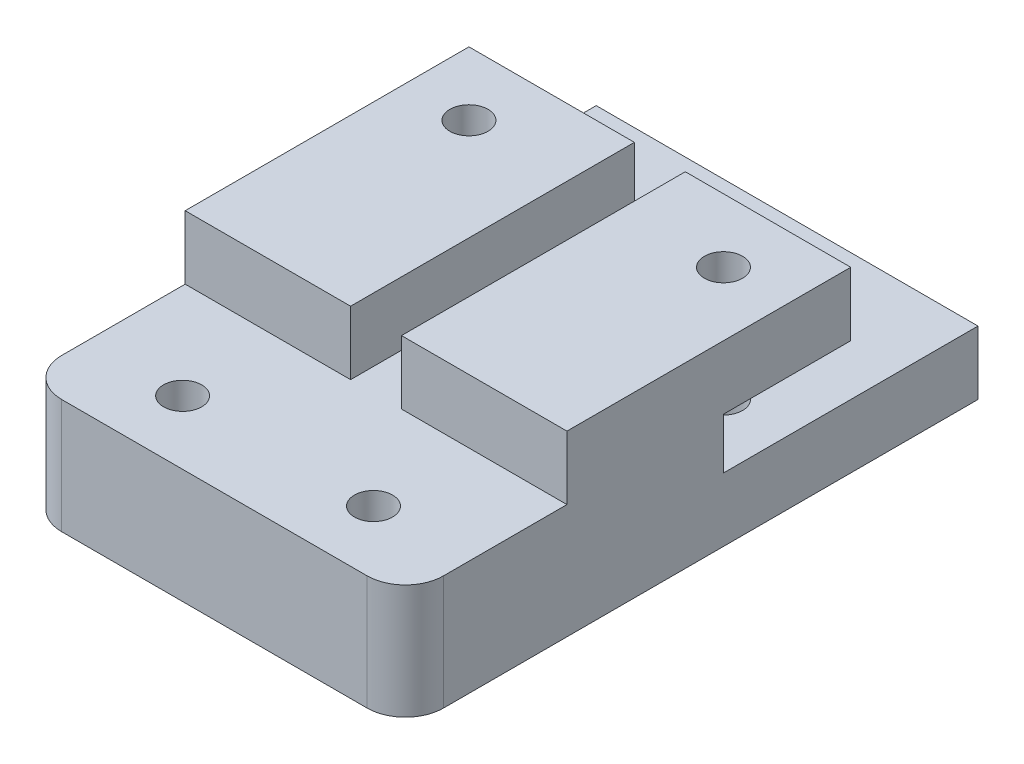
SolidWorks part; units mm, degrees
ref_plane "Alzado" through (0, 0, 0) normal (0, 0, 1) x (1, 0, 0)
ref_plane "Planta" through (0, 0, 0) normal (0, 1, 0) x (1, 0, 0)
ref_plane "Vista lateral" through (0, 0, 0) normal (1, 0, 0) x (0, 0, -1)
sketch "Croquis1" plane through (0, 0, 0) normal (0, 1, 0) x (1, 0, 0)
  line L0 (0, 30) -> (5, 30) construction
  line L1 (0, 0) -> (30, 0)
  line L2 (0, 0) -> (0, 35)
  line L3 (0, 35) -> (30, 35)
  line L4 (30, 0) -> (30, 35)
  line L5 (5, 30) -> (25, 30) construction
  line L6 (25, 30) -> (30, 30) construction
  line L7 (15, 30) -> (15, 35) construction
  line L8 (0, 5) -> (7.5, 5) construction
  line L9 (7.5, 5) -> (22.5, 5) construction
  line L10 (22.5, 5) -> (30, 5) construction
  line L11 (15, 30) -> (15, 5) construction
  circle A0 centre (25, 30) radius 1.5
  circle A1 centre (5, 30) radius 1.5
  circle A2 centre (7.5, 5) radius 1.5
  circle A3 centre (22.5, 5) radius 1.5
  dimension "D3" = 3
  dimension "D6" = 3
  dimension "D1" = 30
  dimension "D2" = 35
  dimension "D4" = 20
  dimension "D5" = 5
  dimension "D7" = 15
  dimension "D8" = 5
extrude "Saliente-Extruir1" add sketch "Croquis1" along normal blind 20
sketch "Croquis2" plane through (30, 0, 0) normal (1, 0, 0) x (0, 0, -1)
  line L0 (35, 20) -> (35, 0) construction
  line L1 (35, 11) -> (25, 11)
  line L2 (35, 11) -> (35, 15)
  line L3 (35, 15) -> (25, 15)
  line L4 (25, 11) -> (25, 15)
  line L5 (0, 20) -> (35, 20) construction
  dimension "D1" = 10
  dimension "D2" = 4
  dimension "D3" = 5
extrude "Cortar-Extruir1" cut sketch "Croquis2" against normal blind 41
sketch "Croquis3" plane through (0, 0, 0) normal (0, -1, 0) x (1, 0, 0)
  line L1 (5, -33.1177) -> (7.7, -31.5588)
  line L2 (7.7, -31.5588) -> (7.7, -28.4412)
  line L3 (7.7, -28.4412) -> (5, -26.8823)
  line L4 (5, -26.8823) -> (2.3, -28.4412)
  line L5 (2.3, -28.4412) -> (2.3, -31.5588)
  line L6 (2.3, -31.5588) -> (5, -33.1177)
  line L7 (25, -33.1177) -> (27.7, -31.5588)
  line L8 (27.7, -31.5588) -> (27.7, -28.4412)
  line L9 (27.7, -28.4412) -> (25, -26.8823)
  line L10 (25, -26.8823) -> (22.3, -28.4412)
  line L11 (22.3, -28.4412) -> (22.3, -31.5588)
  line L12 (22.3, -31.5588) -> (25, -33.1177)
  circle A0 centre (5, -30) radius 2.7 construction
  circle A1 centre (25, -30) radius 2.7 construction
  dimension "D1" = 5.4
extrude "Cortar-Extruir2" cut sketch "Croquis3" against normal blind 8
sketch "Croquis4" plane through (0, 0, 0) normal (0, -1, 0) x (1, 0, 0)
  line L1 (7.5, -8.1177) -> (10.2, -6.5588)
  line L2 (10.2, -6.5588) -> (10.2, -3.4412)
  line L3 (10.2, -3.4412) -> (7.5, -1.8823)
  line L4 (7.5, -1.8823) -> (4.8, -3.4412)
  line L5 (4.8, -3.4412) -> (4.8, -6.5588)
  line L6 (4.8, -6.5588) -> (7.5, -8.1177)
  line L7 (22.5, -8.1177) -> (25.2, -6.5588)
  line L8 (25.2, -6.5588) -> (25.2, -3.4412)
  line L9 (25.2, -3.4412) -> (22.5, -1.8823)
  line L10 (22.5, -1.8823) -> (19.8, -3.4412)
  line L11 (19.8, -3.4412) -> (19.8, -6.5588)
  line L12 (19.8, -6.5588) -> (22.5, -8.1177)
  circle A0 centre (7.5, -5) radius 2.7 construction
  circle A1 centre (22.5, -5) radius 2.7 construction
  dimension "D1" = 5.4
extrude "Cortar-Extruir3" cut sketch "Croquis4" against normal blind 8
sketch "Croquis6" plane through (0, 0, -35) normal (0, 0, -1) x (-1, 0, 0)
  line L4 (0, 0) -> (0, 11)
  line L5 (0, 11) -> (-30, 11)
  line L6 (-30, 11) -> (-30, 0)
  line L7 (-30, 0) -> (0, 0)
  line L8 (0, 0) -> (0, 11)
  line L9 (0, 11) -> (-30, 11)
  line L10 (-30, 11) -> (-30, 0)
  line L11 (-30, 0) -> (0, 0)
  dimension "D1" = 0
extrude "Saliente-Extruir2" add sketch "Croquis6" along normal blind 10
sketch "Croquis7" plane through (0, 0, 0) normal (-1, 0, 0) x (0, 0, 1)
  line L0 (0, 20) -> (0, 0) construction
  line L1 (-45, 0) -> (0, 0)
  line L2 (-45, 0) -> (-45, 6)
  line L3 (-45, 6) -> (0, 6)
  line L4 (0, 0) -> (0, 6)
  dimension "D1" = 6
extrude "Cortar-Extruir4" cut sketch "Croquis7" against normal up to surface (30 mm away)
sketch "Croquis8" plane through (0, 0, -35) normal (0, 0, -1) x (-1, 0, 0)
  line L0 (-15, 20) -> (-15, 15) construction
  line L1 (-30, 20) -> (0, 20) construction
  line L2 (0, 15) -> (-30, 15) construction
  line L3 (0, 15) -> (-30, 15) construction
  line L4 (-17, 20) -> (-13, 20)
  line L5 (-17, 20) -> (-17, 15)
  line L6 (-17, 15) -> (-13, 15)
  line L7 (-13, 20) -> (-13, 15)
  line L8 (-17, 20) -> (-13, 15) construction
  line L9 (-17, 15) -> (-13, 20) construction
  point P6 (-15, 17.5)
  dimension "D1" = 4
extrude "Cortar-Extruir5" cut sketch "Croquis8" against normal up to surface (35 mm away) up to face at (15, 13, 0)
sketch "Croquis9" plane through (0, 0, 0) normal (-1, 0, 0) x (0, 0, 1)
  line L0 (-35, 15) -> (-25, 15) construction
  line L1 (0, 20) -> (-12.7, 20)
  line L2 (0, 20) -> (0, 15)
  line L3 (0, 15) -> (-12.7, 15)
  line L4 (-12.7, 20) -> (-12.7, 15)
  dimension "D1" = 12.7
extrude "Cortar-Extruir6" cut sketch "Croquis9" against normal up to surface (30 mm away)
fillet "Redondeo1" radius 3 2 edges at (30, 10.5, 0) (0, 10.5, 0)
